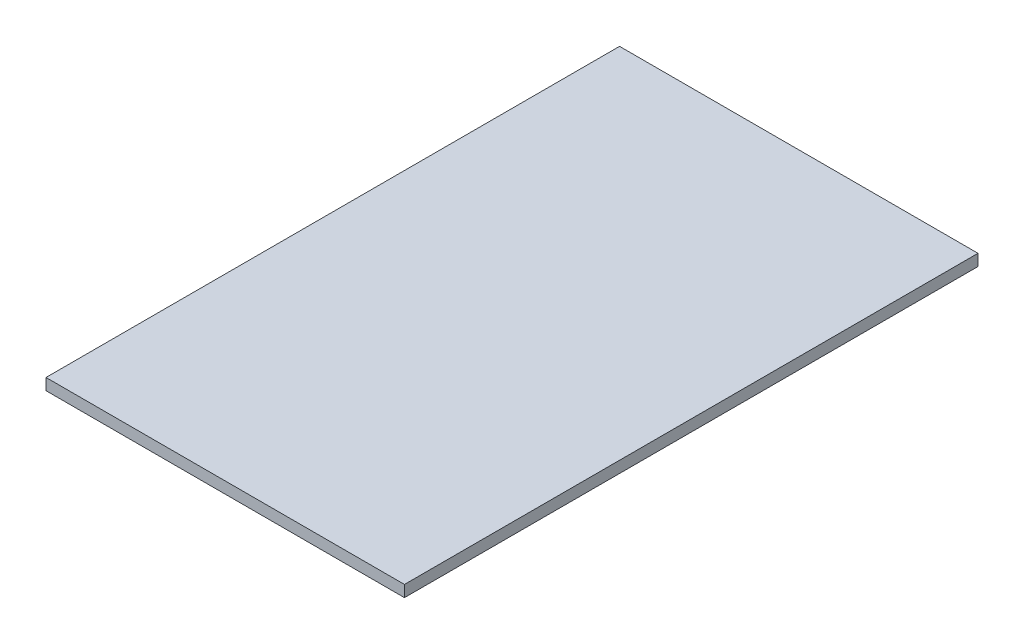
SolidWorks part; units mm, degrees
material "ABS"
ref_plane "Front Plane" through (0, 0, 0) normal (0, 0, 1) x (1, 0, 0)
ref_plane "Top Plane" through (0, 0, 0) normal (0, 1, 0) x (1, 0, 0)
ref_plane "Right Plane" through (0, 0, 0) normal (1, 0, 0) x (0, 0, -1)
sketch "Sketch1" plane through (0, 0, 0) normal (0, 1, 0) x (1, 0, 0)
  line L1 (0, 0) -> (50, 0)
  line L2 (0, 0) -> (0, 80)
  line L3 (0, 80) -> (50, 80)
  line L4 (50, 0) -> (50, 80)
  dimension "D1" = 80
  dimension "D2" = 50
extrude "Boss-Extrude1" add sketch "Sketch1" along normal blind 1.6
